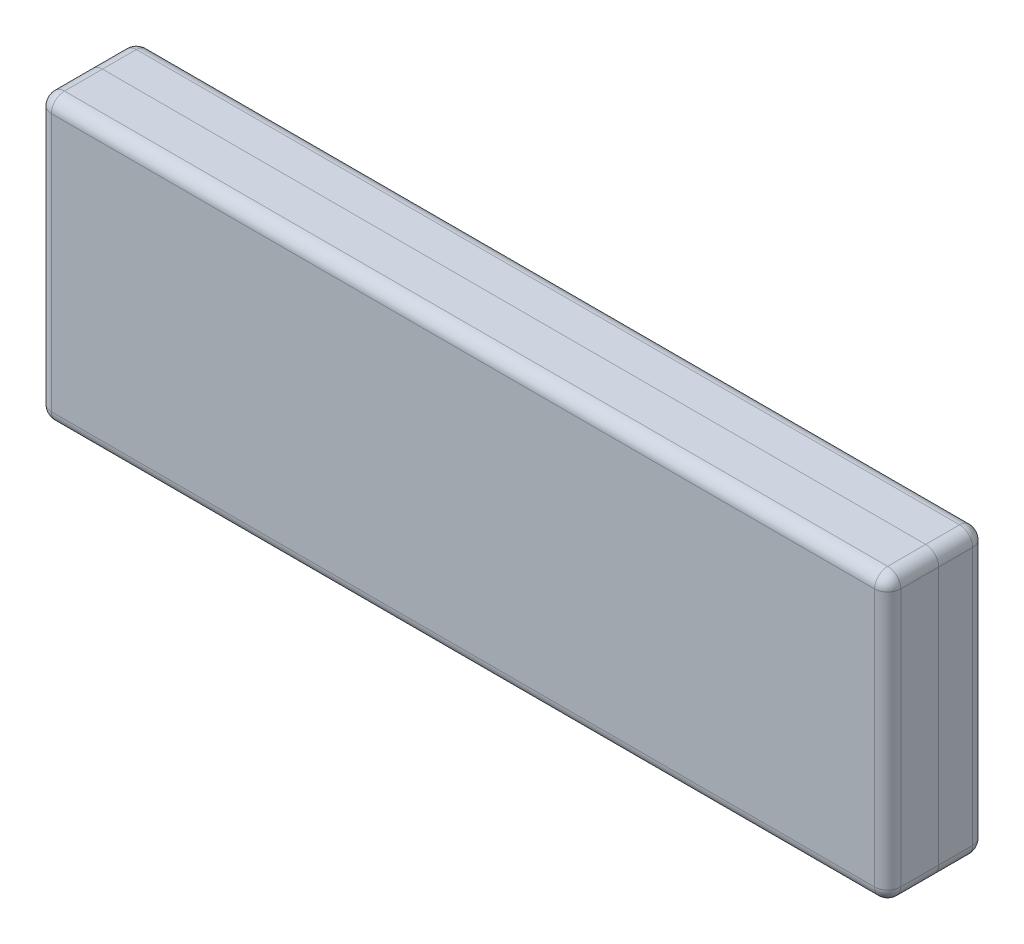
SolidWorks part; units mm, degrees
ref_plane "Front Plane" through (0, 0, 0) normal (0, 0, 1) x (1, 0, 0)
ref_plane "Top Plane" through (0, 0, 0) normal (0, 1, 0) x (1, 0, 0)
ref_plane "Right Plane" through (0, 0, 0) normal (1, 0, 0) x (0, 0, -1)
sketch "Sketch1" plane through (0, 0, 0) normal (0, 0, 1) x (1, 0, 0)
  line L1 (-130, 43.5) -> (130, 43.5)
  line L2 (-130, 43.5) -> (-130, -43.5)
  line L3 (-130, -43.5) -> (130, -43.5)
  line L4 (130, 43.5) -> (130, -43.5)
  line L5 (-130, 43.5) -> (130, -43.5) construction
  line L6 (-130, -43.5) -> (130, 43.5) construction
  point P0 (0, 0)
  dimension "D1" = 87
  dimension "D2" = 260
extrude "Boss-Extrude1" add sketch "Sketch1" along normal blind 30
sketch "Sketch7" plane through (0, -43.5, 0) normal (0, -1, 0) x (1, 0, 0)
  line L0 (-130, 15) -> (130, 15) construction
  line L1 (-130, 30) -> (-130, 0) construction
  line L2 (130, 30) -> (130, 0) construction
  circle A0 centre (-114.25, 15) radius 12.25
  circle A1 centre (-88.85, 15) radius 12.25
  circle A2 centre (-63.45, 15) radius 12.25
  circle A3 centre (-38.05, 15) radius 12.25
  circle A4 centre (-12.65, 15) radius 12.25
  circle A5 centre (12.75, 15) radius 12.25
  circle A6 centre (38.15, 15) radius 12.25
  circle A7 centre (63.55, 15) radius 12.25
  circle A8 centre (88.95, 15) radius 12.25
  circle A9 centre (114.35, 15) radius 12.25
  dimension "D1" = 24.5
  dimension "D2" = 15.75
  dimension "D3" = 10
extrude "Cut-Extrude1" cut sketch "Sketch7" against normal blind 13 from offset 3 offset against normal yes
sketch "Sketch9" plane through (0, 43.5, 0) normal (0, 1, 0) x (1, 0, 0)
  line L0 (-130, -15) -> (130, -15) construction
  line L1 (-130, -30) -> (-130, 0) construction
  line L2 (130, -30) -> (130, 0) construction
  circle A0 centre (-114.25, -15) radius 12.25
  circle A1 centre (-88.85, -15) radius 12.25
  circle A2 centre (-63.45, -15) radius 12.25
  circle A3 centre (-38.05, -15) radius 12.25
  circle A4 centre (-12.65, -15) radius 12.25
  circle A5 centre (12.75, -15) radius 12.25
  circle A6 centre (38.15, -15) radius 12.25
  circle A7 centre (63.55, -15) radius 12.25
  circle A8 centre (88.95, -15) radius 12.25
  circle A9 centre (114.35, -15) radius 12.25
  dimension "D1" = 24.5
  dimension "D2" = 15.75
  dimension "D3" = 10
extrude "Cut-Extrude2" cut sketch "Sketch9" against normal blind 65 from offset 3 offset against normal yes
fillet "Fillet1" radius 4 12 edges at (0, 43.5, 0) (-130, 0, 0) (0, -43.5, 0) (130, 0, 0) (0, -43.5, 30) (-130, 0, 30) (0, 43.5, 30) (130, 0, 30) (-130, 43.5, 15) (130, 43.5, 15) (130, -43.5, 15) (-130, -43.5, 15)
sketch "Sketch3" plane through (0, -43.5, 0) normal (0, -1, 0) x (1, 0, 0)
  line L0 (-145.946, 14.3781) -> (167.0916, 14.3781)
split "Split1" trim tools "Sketch3" bodies to split 103 resulting bodies 104 105
